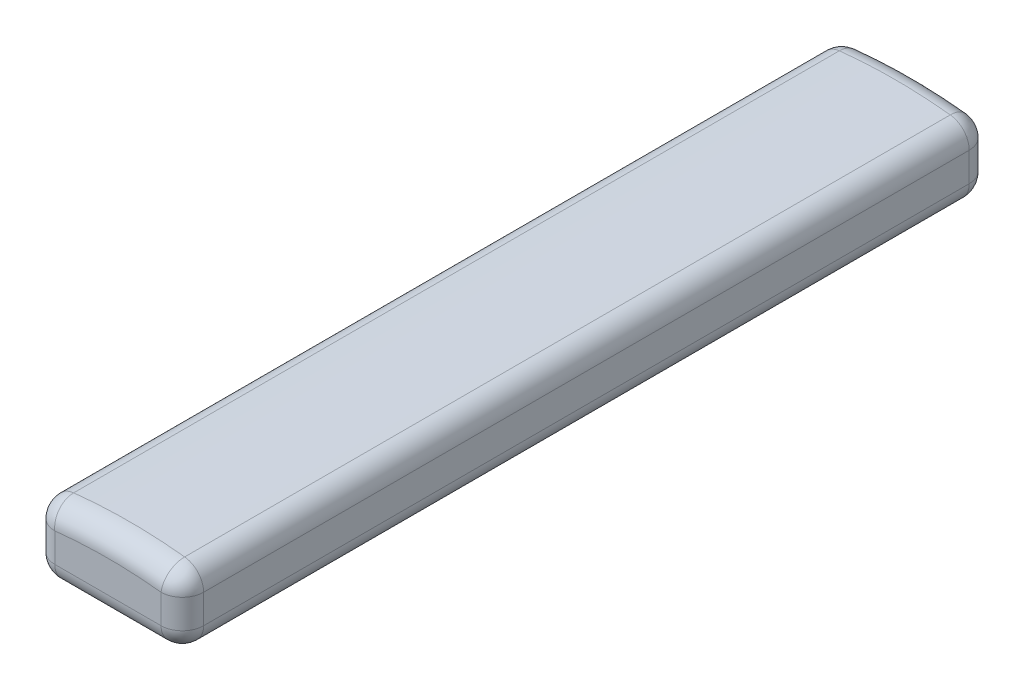
SolidWorks part; units mm, degrees
material "Nickel"
ref_plane "Front" through (0, 0, 0) normal (0, 0, 1) x (1, 0, 0)
ref_plane "Top" through (0, 0, 0) normal (0, 1, 0) x (1, 0, 0)
ref_plane "Right" through (0, 0, 0) normal (1, 0, 0) x (0, 0, -1)
sketch "Sketch1" plane through (0, 0, 0) normal (0, 0, 1) x (1, 0, 0)
  line L1 (-3.5, -1.75) -> (3.5, -1.75)
  line L2 (-3.5, -1.75) -> (-3.5, 1.75)
  line L3 (-3.5, 1.75) -> (3.5, 1.75)
  line L4 (3.5, -1.75) -> (3.5, 1.75)
  line L5 (-3.5, -1.75) -> (3.5, 1.75) construction
  line L6 (-3.5, 1.75) -> (3.5, -1.75) construction
  point P0 (0, 0)
  dimension "D1" = 7
  dimension "D2" = 3.5
extrude "Boss-Extrude1" add sketch "Sketch1" along normal blind 38
sketch "Sketch2" plane through (0, 0, 38) normal (0, 0, 1) x (1, 0, 0)
  line L0 (3.5, 1.75) -> (-3.5, 1.75) construction
  circle A0 centre (0, -22.25) radius 24
  circle A1 centre (0, -22.25) radius 29
  point P4 (0, 1.75)
  dimension "D1" = 48
  dimension "D2" = 5
extrude "Cut-Extrude1" cut sketch "Sketch2" against normal through all
fillet "Fillet1" radius 1 12 edges at (-3.5, -1.75, 19) (0, -1.75, 38) (3.5, -1.75, 19) (0, -1.75, 0) (0, 1.75, 0) (3.5, -0.1283, 0) (3.5, 1.4934, 19) (-3.5, -0.1283, 0) (-3.5, 1.4934, 19) (3.5, -0.1283, 38) (-3.5, -0.1283, 38) (0, 1.75, 38)
